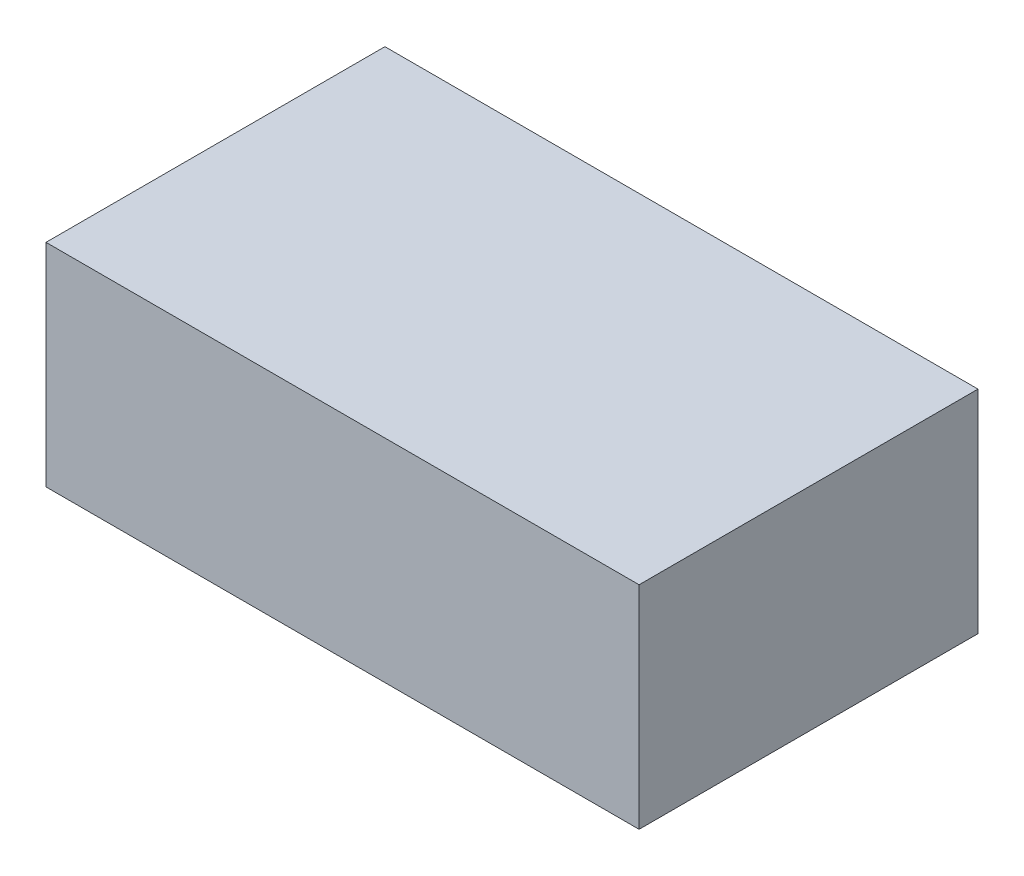
SolidWorks part; units mm, degrees
ref_plane "Front Plane" through (0, 0, 0) normal (0, 0, 1) x (1, 0, 0)
ref_plane "Top Plane" through (0, 0, 0) normal (0, 1, 0) x (1, 0, 0)
ref_plane "Right Plane" through (0, 0, 0) normal (1, 0, 0) x (0, 0, -1)
sketch "Sketch1" plane through (0, 0, 0) normal (0, 1, 0) x (1, 0, 0)
  line L1 (0, 0) -> (-44.45, 0)
  line L2 (0, 0) -> (0, 25.4)
  line L3 (0, 25.4) -> (-44.45, 25.4)
  line L4 (-44.45, 0) -> (-44.45, 25.4)
  dimension "D1" = 44.45
  dimension "D2" = 25.4
extrude "Boss-Extrude1" add sketch "Sketch1" along normal blind 15.875
